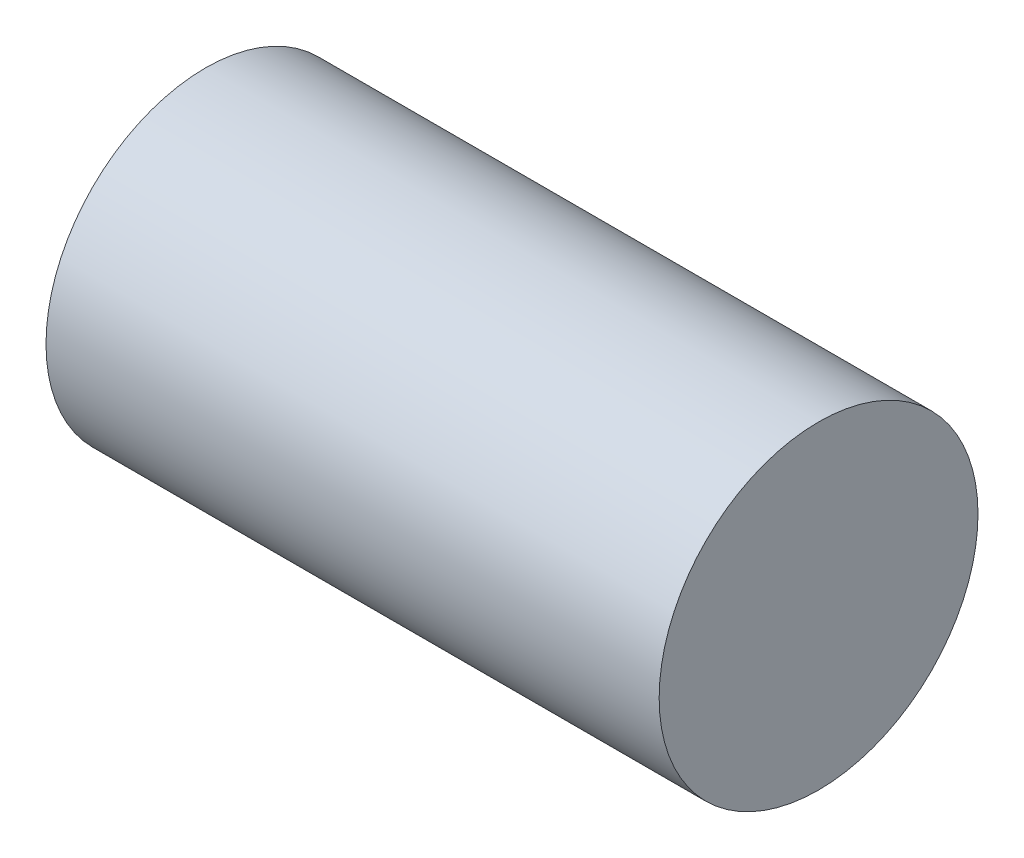
SolidWorks part; units mm, degrees
ref_plane "Přední rovina" through (0, 0, 0) normal (0, 0, 1) x (1, 0, 0)
ref_plane "Horní rovina" through (0, 0, 0) normal (0, 1, 0) x (1, 0, 0)
ref_plane "Pravá rovina" through (0, 0, 0) normal (1, 0, 0) x (0, 0, -1)
sketch "Skica1" plane through (0, 0, 0) normal (1, 0, 0) x (0, 0, -1)
  circle A0 centre (0, 0) radius 26
  dimension "D1" = 52
extrude "Přidat vysunutím1" add sketch "Skica1" against normal blind 100
sketch "Skica2" plane through (0, 0, 0) normal (0, 0, 1) x (1, 0, 0)
  line L0 (0, 65) -> (0, -65)
  line L1 (0, 0) -> (65, 0) construction
  line L2 (57.6346, 6.5) -> (64.6742, 6.5)
  line L3 (57.6346, -6.5) -> (64.6742, -6.5)
  line L4 (46.663, -34.4465) -> (52.7595, -37.9663)
  line L5 (53.163, -23.1881) -> (59.2595, -26.7079)
  line L7 (23.1881, -53.163) -> (26.7079, -59.2595)
  line L8 (34.4465, -46.663) -> (37.9663, -52.7595)
  line L11 (0, 0) -> (46.663, -34.4465) construction
  line L12 (32.5, 56.2917) -> (-32.5, -56.2917)
  line L13 (56.2917, 32.5) -> (-56.2917, -32.5)
  line L14 (53.163, 23.1881) -> (59.2595, 26.7079)
  line L15 (46.663, 34.4465) -> (52.7595, 37.9663)
  line L16 (23.1881, 53.163) -> (26.7079, 59.2595)
  line L17 (34.4465, 46.663) -> (37.9663, 52.7595)
  arc A0 (0, -58) -> (0, 58) centre (0, 0) ccw
  arc A1 (0, -65) -> (0, 65) centre (0, 0) ccw
  arc A3 (0, -65) -> (56.2917, 32.5) centre (0, 0) ccw
  arc A4 (-32.5, -56.2917) -> (32.5, 56.2917) centre (0, 0) ccw
  point P26 (0, 0)
  dimension "D2" = 65
  dimension "D3" = 58
  dimension "D1" = 13
  dimension "D4" = 3
